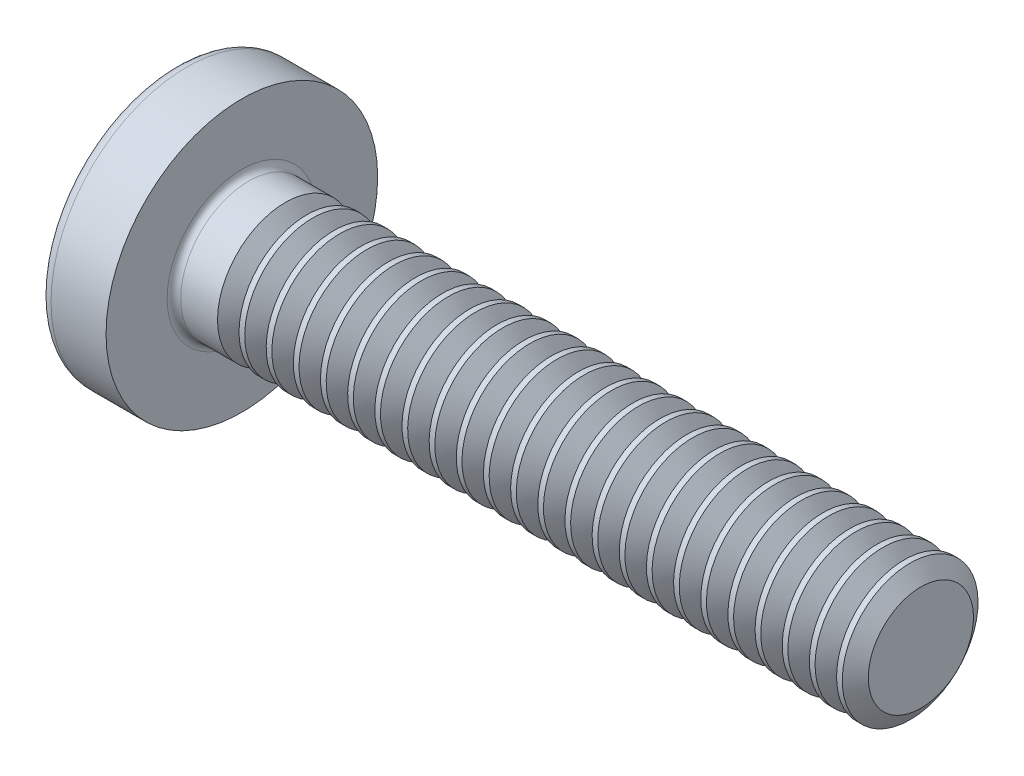
SolidWorks part; units mm, degrees
ref_plane "Plane1" through (0, 0, 0) normal (0, 0, 1) x (1, 0, 0)
ref_plane "Plane2" through (0, 0, 0) normal (0, 1, 0) x (1, 0, 0)
ref_plane "Plane3" through (0, 0, 0) normal (1, 0, 0) x (0, 0, -1)
sketch "BodySke" plane through (0, 0, 0) normal (0, 0, 1) x (1, 0, 0)
  line L0 (1.6, 1) -> (1.6, 2)
  line L1 (1.8, 6.35) -> (1.8, -3.175) construction
  line L2 (-25.4, 0) -> (127, 0) construction
  line L3 (11.6, 0) -> (0, 0)
  line L4 (1.6, 1) -> (11.6, 1)
  line L5 (11.6, 1) -> (11.6, 0)
  line L6 (0.79, 2) -> (1.6, 2)
  line L8 (1.6, 6.35) -> (1.6, -3.175) construction
  arc A0 (0.6464, 1.9285) -> (0, 0) centre (3.2, 0) ccw
  arc A2 (0.6464, 1.9285) -> (0.79, 2) centre (0.79, 1.82) cw
  dimension "Head_crown_rad" = 3.2
  dimension "Head_fillet_rad" = 0.18
  dimension "Length" = 10
  dimension "Head_ht" = 1.6
  dimension "Head_dia" = 4
  dimension "Advance" = 0.4
  dimension "Thread_nom" = 10
  dimension "Diameter" = 2
revolve "Base-Revolve" add sketch "BodySke"
cosmetic thread "ThreadCosmetic" [suppressed]
fillet "Fillet1" radius 0.1 1 edges at (1.6, 0, 1)
sketch "Sketch3" plane through (0, 0, 0) normal (1, 0, 0) x (0, 0, -1)
  line L0 (0.24, -1.05) -> (-0.24, -1.05)
  line L1 (0.24, -1.05) -> (0.24, 1.05)
  line L2 (-0.24, 1.05) -> (0.24, 1.05)
  line L3 (-0.24, 1.05) -> (-0.24, -1.05)
  dimension "Cross_dia" = 2.1
  dimension "D1" = 1.05
  dimension "Cross_width" = 0.48
  dimension "D2" = 0.24
ref_plane "Plane4" through (1.42, 0, 0) normal (1, 0, 0) x (0, 0, -1)
sketch "Sketch4" plane through (1.42, 0, 0) normal (1, 0, 0) x (0, 0, -1)
  line L0 (0.24, -0.342) -> (-0.24, -0.342)
  line L1 (0.24, -0.342) -> (0.24, 0.342)
  line L2 (-0.24, 0.342) -> (0.24, 0.342)
  line L3 (-0.24, 0.342) -> (-0.24, -0.342)
  dimension "D1" = 0.48
  dimension "D2" = 0.684
  dimension "D3" = 0.24
  dimension "D4" = 0.342
loft "Recess" cut profiles "Sketch3", "Sketch4"
pattern_circular "RecPat" count 2 every 90 about axis through (0, 0, 0) along (1, 0, 0) of "Recess"
sketch "RecCorSke" plane through (0, 0, 0) normal (0, 0, 1) x (1, 0, 0)
  line L0 (-3.175, 0) -> (15.875, 0) construction
  line L1 (-25.4, 0) -> (127, 0) construction
  line L2 (0, 0) -> (0, 0.4548)
  line L3 (0, 0.4548) -> (1.42, 0.3555)
  line L4 (1.42, 0.3555) -> (1.5355, 0)
  line L5 (1.5355, 0) -> (0, 0)
  dimension "Diameter" = 0.711
  dimension "Depth" = 1.42
  dimension "Draft_angle" = 4
  dimension "Bottom_angle" = 18
revolve "RecessCore" cut sketch "RecCorSke" angle 360 about L0
sketch "ThdSchSke" plane through (0, 0, 0) normal (0, 0, 1) x (1, 0, 0)
  line L0 (2.4, -0.774) -> (2.2418, -1)
  line L1 (2.4, -0.774) -> (2.5582, -1)
  line L2 (2.5582, -1) -> (2.5582, -1.25)
  line L3 (-3.175, 0) -> (5.1513, 0) construction
  line L5 (2.5582, -1.25) -> (2.2418, -1.25)
  line L6 (2.2418, -1.25) -> (2.2418, -1)
  dimension "Diameter" = 2
  dimension "SideAngle" = 55
  dimension "VeeAngle" = 70
  dimension "Thread_minor" = 1.548
  dimension "Overcut" = 2.5
  dimension "Start" = 2.4
revolve "ThreadSchematic" cut sketch "ThdSchSke" angle 360 about L3
pattern_linear "ThdSchPat" count 24 spacing 0.4 along (1, 0, 0) of "ThreadSchematic"
equation "\"D1@Sketch3\" = \"Cross_dia@Sketch3\" / 2"
equation "\"D2@Sketch3\" = \"Cross_width@Sketch3\" / 2"
equation "\"Depth@RecCorSke\" = \"Cross_depth@Plane4\""
equation "\"D1@Sketch4\" = \"Cross_width@Sketch3\""
equation "\"D2@Sketch4\" = \"Cross_dia@Sketch3\" - 2.0 * \"Cross_depth@Plane4\" * tan(26.5  * 0.017453292)"
equation "\"D3@Sketch4\" = \"D1@Sketch4\" / 2"
equation "\"D4@Sketch4\" = \"D2@Sketch4\" / 2"
equation "\"Thread_length@ThreadCosmetic\" = ((sgn( (\"Length@BodySke\" - \"Advance@BodySke\" * 2.0 ) - \"Thread_nom@BodySke\" )-1)*( (\"Length@BodySke\" - \"Advance@BodySke\" * 2.0 ) - \"Thread_nom@BodySke\" ))/-2+ \"Thread_nom@BodySke\""
equation "\"Thread_minor@ThdSchSke\" = \"Thread_minor@ThreadCosmetic\""
equation "\"Diameter@ThdSchSke\" = \"Diameter@BodySke\""
equation "\"Overcut@ThdSchSke\" = \"Diameter@BodySke\" * 1.25"
equation "\"Start@ThdSchSke\" = \"Head_ht@BodySke\" + \"Length@BodySke\" - \"Thread_length@ThreadCosmetic\"  '---Non-countersunk---"
equation "\"Num_threads@ThdSchPat\" = int( \"Thread_length@ThreadCosmetic\" / \"Advance@BodySke\" + 0.999 )  + 1"
equation "\"Advance@ThdSchPat\" = \"Thread_length@ThreadCosmetic\" /  (\"Num_threads@ThdSchPat\" - 1) 'relax it"
